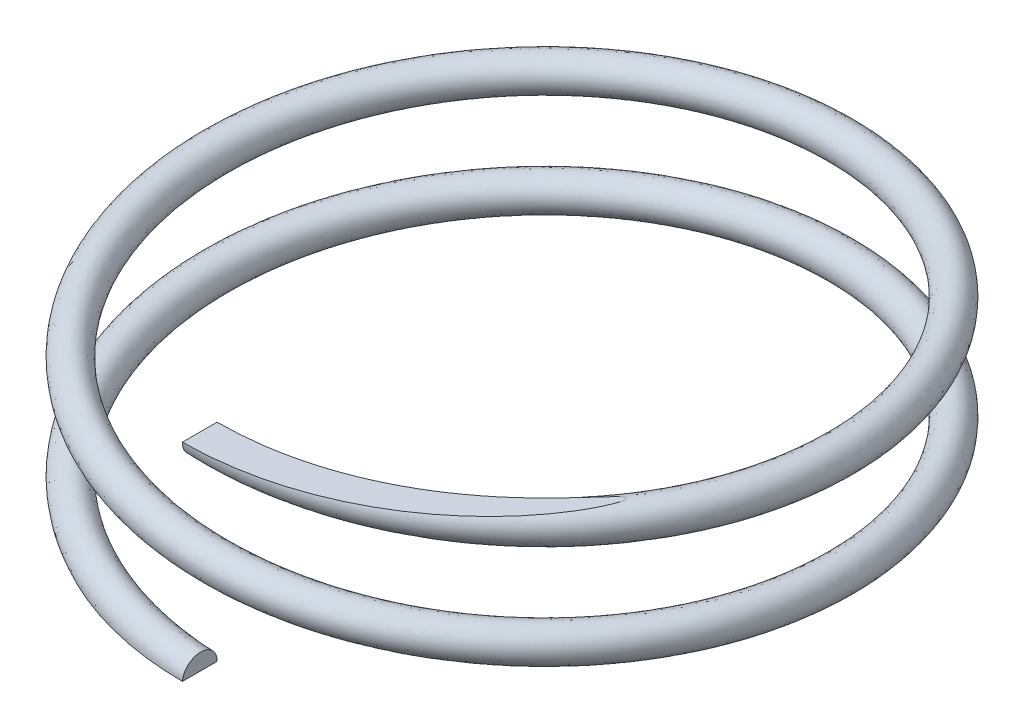
SolidWorks part; units mm, degrees
material "Сталь 3 ГОСТ 535-88"
ref_plane "Спереди" through (0, 0, 0) normal (0, 0, 1) x (1, 0, 0)
ref_plane "Сверху" through (0, 0, 0) normal (0, 1, 0) x (1, 0, 0)
ref_plane "Справа" through (0, 0, 0) normal (1, 0, 0) x (0, 0, -1)
sketch "Эскиз2" plane through (0, 0, 0) normal (0, 1, 0) x (1, 0, 0)
  circle A0 centre (0, 0) radius 45
  dimension "D1" = 90
curve "Спираль1" pitch 15 height 30 turns 2
ref_plane "Плоскость1" through (0, 0, 45) normal (-0.9986, 0.053, 0) x (0, 0, 1)
sketch "Эскиз3" plane through (0, 0, 45) normal (-0.9986, 0.053, 0) x (0, 0, 1)
  circle A0 centre (0.197, 0) radius 2.5
  dimension "D1" = 5
sweep "По траектории1" add profiles "Эскиз3" path "Спираль1"
sketch "Эскиз4" plane through (0, 0, 0) normal (0, 1, 0) x (1, 0, 0)
  line L1 (-63.7664, 67.7576) -> (70.4263, 67.7576)
  line L2 (-63.7664, 67.7576) -> (-63.7664, -67.7576)
  line L3 (-63.7664, -67.7576) -> (70.4263, -67.7576)
  line L4 (70.4263, 67.7576) -> (70.4263, -67.7576)
  line L5 (3.33, -67.7576) -> (3.33, 67.7576) construction
  line L6 (-63.7664, 0) -> (70.4263, 0) construction
  point P0 (3.33, 0)
  point P4 (3.33, 2.6061)
  point P5 (-63.7664, 0)
extrude "Вырез-Вытянуть1" cut sketch "Эскиз4" against normal through all
ref_plane "Плоскость2" through (0, 30, 0) normal (0, 1, 0) x (1, 0, 0)
sketch "Эскиз5" plane through (0, 30, 0) normal (0, 1, 0) x (1, 0, 0)
  line L4 (70.4263, 67.7576) -> (-63.7664, 67.7576)
  line L5 (-63.7664, 67.7576) -> (-63.7664, -67.7576)
  line L6 (-63.7664, -67.7576) -> (70.4263, -67.7576)
  line L7 (70.4263, -67.7576) -> (70.4263, 67.7576)
  line L8 (70.4263, 67.7576) -> (-63.7664, 67.7576)
  line L9 (-63.7664, 67.7576) -> (-63.7664, -67.7576)
  line L10 (-63.7664, -67.7576) -> (70.4263, -67.7576)
  line L11 (70.4263, -67.7576) -> (70.4263, 67.7576)
  dimension "D1" = 0
extrude "Вырез-Вытянуть2" cut sketch "Эскиз5" along normal through all
